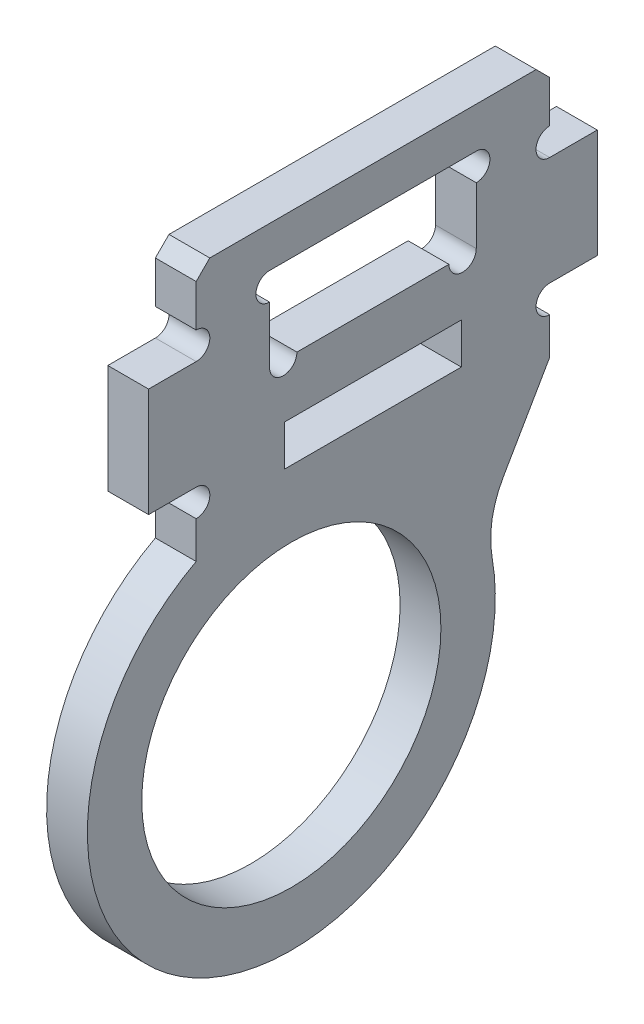
SolidWorks part; units mm, degrees
material "Thornel Mat VMA"
ref_plane "前视基准面" through (0, 0, 0) normal (0, 0, 1) x (1, 0, 0)
ref_plane "上视基准面" through (0, 0, 0) normal (0, 1, 0) x (1, 0, 0)
ref_plane "右视基准面" through (0, 0, 0) normal (1, 0, 0) x (0, 0, -1)
sketch "草图1" plane through (0, 0, 0) normal (1, 0, 0) x (0, 0, -1)
  line L0 (-13, 6.1) -> (13, 6.1)
  line L1 (7.6, -3.1) -> (-7.6, -3.1)
  line L2 (7.6, -3.1) -> (7.6, 3.1)
  line L3 (7.6, 3.1) -> (-7.6, 3.1)
  line L4 (-7.6, -3.1) -> (-7.6, 3.1)
  line L5 (7.6, -3.1) -> (-7.6, 3.1) construction
  line L6 (7.6, 3.1) -> (-7.6, -3.1) construction
  line L7 (13, 6.1) -> (13, 0)
  line L8 (0, 0) -> (0, -16.3564) construction
  line L9 (-13, 6.1) -> (-13, 0)
  line L10 (13, 0) -> (16.5, 0)
  line L11 (16.5, 0) -> (16.5, -8)
  line L12 (16.5, -8) -> (13, -8)
  line L13 (-16.5, -8) -> (-13, -8)
  line L14 (-16.5, 0) -> (-16.5, -8)
  line L15 (-13, 0) -> (-16.5, 0)
  line L16 (-13, -8) -> (-13, -12.7335)
  line L18 (16.5, -4) -> (10.4606, -4) construction
  line L19 (13, -8) -> (13, -12.7335)
  line L20 (6.5, -10.1) -> (-6.5, -10.1)
  line L21 (6.5, -10.1) -> (6.5, -7.1)
  line L22 (6.5, -7.1) -> (-6.5, -7.1)
  line L23 (-6.5, -10.1) -> (-6.5, -7.1)
  line L24 (6.5, -10.1) -> (-6.5, -7.1) construction
  line L25 (6.5, -7.1) -> (-6.5, -10.1) construction
  line L26 (13, -12.7335) -> (8.1743, -21.0919)
  circle A2 centre (6.595, -3.1) radius 1.005
  circle A3 centre (-6.595, -3.1) radius 1.005
  circle A4 centre (-6, -26) radius 11
  circle A6 centre (7.6, 2.095) radius 1.005
  circle A7 centre (-7.6, 2.095) radius 1.005
  circle A8 centre (-13, 1.005) radius 1.005
  circle A9 centre (-13, -9.005) radius 1.005
  circle A10 centre (13, -9.005) radius 1.005
  circle A11 centre (13, 1.005) radius 1.005
  arc A12 (-13, -12.7335) -> (8.1743, -21.0919) centre (-6, -26) ccw
  point P0 (0, 0)
  point P40 (0, -8.6)
  dimension "D3" = 22
  dimension "D5" = 2.01
  dimension "D6" = 6
  dimension "D15" = 4
  dimension "D1" = 15.2
  dimension "D2" = 6.2
  dimension "D4" = 26
  dimension "D7" = 26
  dimension "D8" = 3
  dimension "D9" = 3.5
  dimension "D10" = 8
  dimension "D11" = 4
  dimension "D12" = 4
  dimension "D13" = 13
  dimension "D14" = 3
  dimension "D16" = 30
extrude "凸台-拉伸1" add sketch "草图1" along normal blind 3
fillet "圆角1" radius 7 1 edges at (1.5, -21.0919, -8.1743)
chamfer "倒角1" distance 1 angle 45 2 edges at (1.5, 6.1, -13) (1.5, 6.1, 13)
